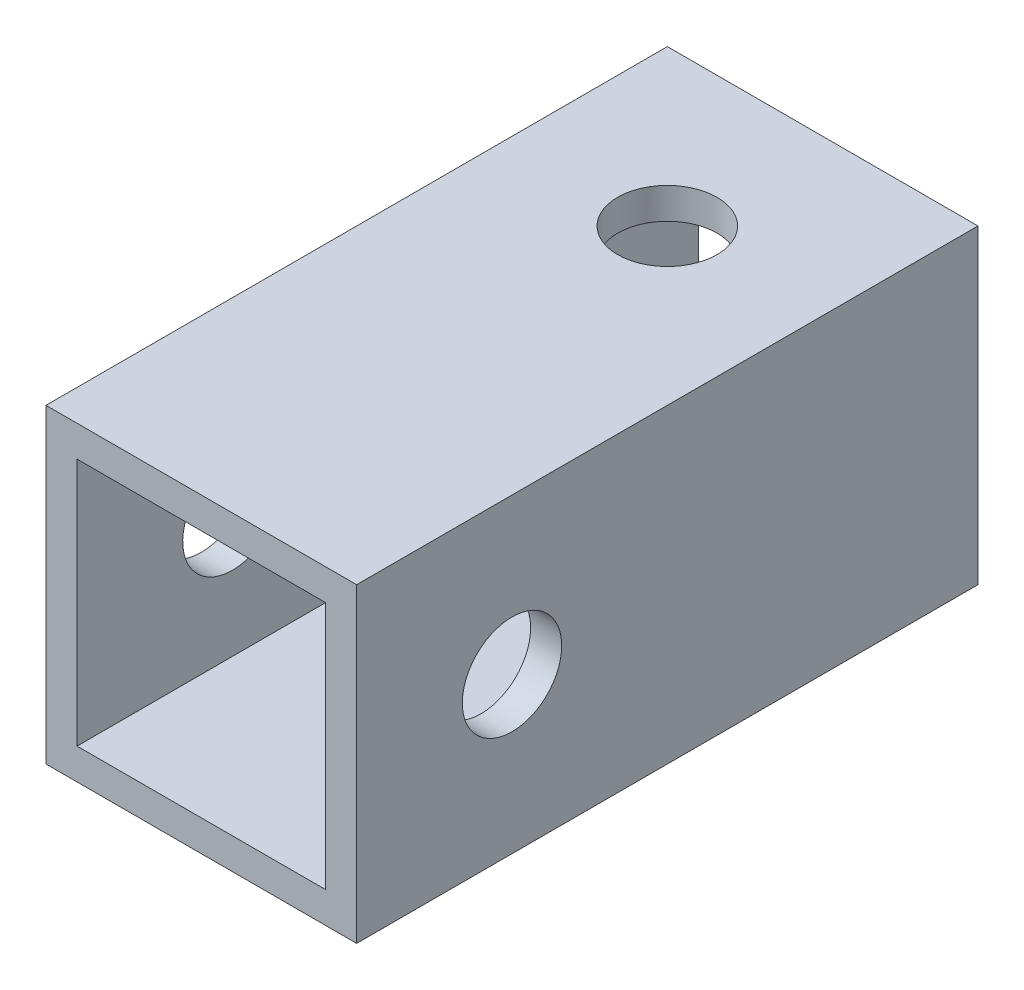
SolidWorks part; units mm, degrees
ref_plane "正面" through (0, 0, 0) normal (0, 0, 1) x (1, 0, 0)
ref_plane "平面" through (0, 0, 0) normal (0, 1, 0) x (1, 0, 0)
ref_plane "右側面" through (0, 0, 0) normal (1, 0, 0) x (0, 0, -1)
sketch "ｽｹｯﾁ1" plane through (0, 0, 0) normal (0, 0, 1) x (1, 0, 0)
  line L0 (-4, 4) -> (-4, -4)
  line L1 (-5, 5) -> (5, 5)
  line L2 (-5, 5) -> (-5, -5)
  line L3 (-5, -5) -> (5, -5)
  line L4 (5, 5) -> (5, -5)
  line L5 (-5, 5) -> (5, -5) construction
  line L6 (-5, -5) -> (5, 5) construction
  line L7 (-4, -4) -> (4, -4)
  line L8 (4, 4) -> (4, -4)
  line L9 (-4, 4) -> (4, 4)
  point P0 (0, 0)
  dimension "D1" = 10
  dimension "D2" = 10
  dimension "D3" = 1
extrude "ﾎﾞｽ - 押し出し1" add sketch "ｽｹｯﾁ1" along normal blind 20
sketch "ｽｹｯﾁ3" plane through (0, 5, 0) normal (0, 1, 0) x (1, 0, 0)
  line L0 (0, -5.5) -> (0, 5.5) construction
  line L1 (-5.5, 0) -> (5.5, 0) construction
  circle A0 centre (0, -5) radius 1.6
  dimension "D1" = 3.2
  dimension "D2" = 5
extrude "ｶｯﾄ - 押し出し1" cut sketch "ｽｹｯﾁ3" against normal through all
sketch "ｽｹｯﾁ4" plane through (-5, 0, 0) normal (-1, 0, 0) x (0, 0, 1)
  line L0 (5.5, 0) -> (-5.5, 0) construction
  line L1 (20, 5) -> (20, -5) construction
  circle A0 centre (15, 0) radius 1.6
  dimension "D1" = 3.2
  dimension "D2" = 5
extrude "ｶｯﾄ - 押し出し2" cut sketch "ｽｹｯﾁ4" against normal through all
